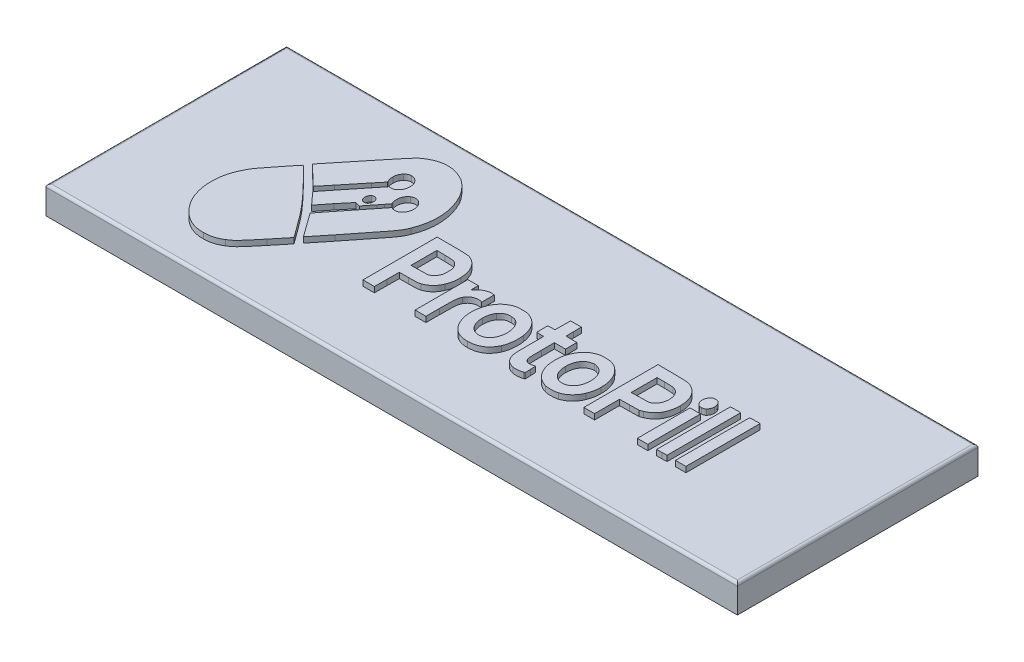
SolidWorks part; units mm, degrees
ref_plane "Front Plane" through (0, 0, 0) normal (0, 0, 1) x (1, 0, 0)
ref_plane "Top Plane" through (0, 0, 0) normal (0, 1, 0) x (1, 0, 0)
ref_plane "Right Plane" through (0, 0, 0) normal (1, 0, 0) x (0, 0, -1)
sketch "Sketch1" plane through (0, 0, 0) normal (0, 1, 0) x (1, 0, 0)
  line L1 (125, -43.5) -> (-125, -43.5)
  line L2 (125, -43.5) -> (125, 43.5)
  line L3 (125, 43.5) -> (-125, 43.5)
  line L4 (-125, -43.5) -> (-125, 43.5)
  line L5 (125, -43.5) -> (-125, 43.5) construction
  line L6 (125, 43.5) -> (-125, -43.5) construction
  point P0 (0, 0)
extrude "Boss-Extrude1" add sketch "Sketch1" along normal blind 10
sketch "Sketch3" plane through (0, 10, 0) normal (0, 1, 0) x (1, 0, 0)
  line L0 (-79.5674, 10.7697) -> (-81.0656, 8.9206)
  line L1 (-81.0656, 8.9206) -> (-79.1545, 7.0857)
  line L2 (-64.4672, 13.6773) -> (-61.8247, 16.8672)
  line L3 (-61.8247, 16.8672) -> (-62.155, 17.5588)
  line L4 (-59.4299, 15.6251) -> (-60.1731, 15.6251)
  line L5 (-60.1731, 15.6251) -> (-61.6949, 13.7055)
  line L6 (-70.9792, -1.2137) -> (-69.5989, -2.7522)
  line L7 (-69.5989, -2.7522) -> (-66.3902, 1.1858)
  line L8 (-62.8039, 5.646) -> (-62.4264, 6.1683)
  line L9 (-62.4264, 6.1683) -> (-62.6033, 6.8175)
  line L10 (-73.952, 2.1173) -> (-72.3476, 0.3954)
  line L11 (-56.5986, 7.8479) -> (-55.4307, 9.3441)
  line L12 (-55.4307, 9.3441) -> (-54.2746, 10.8543)
  line L13 (-54.2746, 10.8543) -> (-54.5224, 11.546)
  line L14 (-52.6467, 9.4429) -> (-53.0831, 9.5981)
  line L15 (-53.0831, 9.5981) -> (-54.0859, 8.356)
  line L16 (-73.4919, 9.6687) -> (-75.757, 6.8599)
  line L17 (-75.757, 6.8599) -> (-76.6535, 7.8338)
  line L18 (-35.659, -4.8271) -> (-35.659, -18.2361)
  line L19 (-35.659, -18.2361) -> (-33.5945, -18.2361)
  line L20 (-33.5945, -18.2361) -> (-31.53, -18.2361)
  line L21 (-31.53, -18.2361) -> (-31.5064, -13.7476)
  line L22 (-31.5064, -13.7476) -> (-31.471, -9.2732)
  line L23 (-31.471, -9.2732) -> (-28.1679, -9.2591)
  line L24 (-30.3149, 8.5819) -> (-35.659, 8.5819)
  line L25 (-35.659, 8.5819) -> (-35.659, -4.8271)
  line L26 (-24.7821, -4.5025) -> (-25.4546, -4.8977)
  line L27 (-25.4546, -4.8977) -> (-28.4864, -4.94)
  line L28 (-28.4864, -4.94) -> (-31.53, -4.9824)
  line L29 (-31.53, -4.9824) -> (-31.53, -0.3104)
  line L30 (-31.53, -0.3104) -> (-31.53, 4.3757)
  line L31 (-31.53, 4.3757) -> (-28.5454, 4.3192)
  line L32 (44.2067, -4.813) -> (44.2067, -18.2361)
  line L33 (44.2067, -18.2361) -> (46.1532, -18.2361)
  line L34 (46.1532, -18.2361) -> (48.0997, -18.2361)
  line L35 (48.0997, -18.2361) -> (48.0997, -13.7335)
  line L36 (48.0997, -13.7335) -> (48.0997, -9.2309)
  line L37 (48.0997, -9.2309) -> (51.6152, -9.1744)
  line L38 (51.6152, -9.1744) -> (55.1189, -9.118)
  line L39 (55.1189, -9.118) -> (56.2279, -8.6663)
  line L40 (49.5508, 8.5536) -> (44.2067, 8.596)
  line L41 (44.2067, 8.596) -> (44.2067, -4.813)
  line L42 (51.2613, -4.94) -> (48.0997, -4.9824)
  line L43 (48.0997, -4.9824) -> (48.0997, -0.3245)
  line L44 (48.0997, -0.3245) -> (48.0997, 4.3475)
  line L45 (48.0997, 4.3475) -> (50.7187, 4.3475)
  line L46 (70.9033, 8.469) -> (70.514, 8.4266)
  line L47 (70.514, 8.4266) -> (70.514, -4.9118)
  line L48 (70.514, -4.9118) -> (70.514, -18.2502)
  line L49 (70.514, -18.2502) -> (72.378, -18.2078)
  line L50 (72.378, -18.2078) -> (74.2301, -18.1655)
  line L51 (74.2301, -18.1655) -> (74.2301, -4.8412)
  line L52 (74.2301, -4.8412) -> (74.2301, 8.4831)
  line L53 (74.2301, 8.4831) -> (72.7555, 8.4972)
  line L54 (77.3563, -4.9259) -> (77.3563, -18.2361)
  line L55 (77.3563, -18.2361) -> (79.2438, -18.2361)
  line L56 (79.2438, -18.2361) -> (81.1313, -18.2361)
  line L57 (81.1313, -18.2361) -> (81.1313, -4.8271)
  line L58 (81.1313, -4.8271) -> (81.1313, 8.596)
  line L59 (81.1313, 8.596) -> (79.3146, 8.5678)
  line L60 (-65.8121, -22.8233) -> (-61.4, -17.4456)
  line L61 (-61.4, -17.4456) -> (-62.7095, -15.6107)
  line L62 (-85.5603, -0.508) -> (-82.3397, 3.5288)
  line L63 (-82.3397, 3.5288) -> (-81.4195, 2.4279)
  line L64 (-81.4195, 2.4279) -> (-80.4994, 1.341)
  line L65 (-80.4994, 1.341) -> (-81.2308, 0.3812)
  line L66 (14.6906, 3.6841) -> (14.6552, 0.8894)
  line L67 (14.6552, 0.8894) -> (13.3812, 0.847)
  line L68 (13.3812, 0.847) -> (12.1071, 0.8047)
  line L69 (12.1071, 0.8047) -> (12.1425, -1.1996)
  line L70 (12.1425, -1.1996) -> (12.1779, -3.2039)
  line L71 (12.1779, -3.2039) -> (13.4519, -3.2462)
  line L72 (13.4519, -3.2462) -> (14.7142, -3.2886)
  line L73 (14.7142, -3.2886) -> (14.7142, -8.3981)
  line L74 (22.2761, -18.0808) -> (22.689, -17.9255)
  line L75 (22.689, -17.9255) -> (22.6418, -15.9918)
  line L76 (18.6308, -8.0311) -> (18.5954, -3.2745)
  line L77 (18.5954, -3.2745) -> (20.6009, -3.2745)
  line L78 (20.6009, -3.2745) -> (22.6182, -3.2745)
  line L79 (22.6182, -3.2745) -> (22.6182, -1.2278)
  line L80 (22.6182, -1.2278) -> (22.6182, 0.8188)
  line L81 (22.6182, 0.8188) -> (20.6481, 0.847)
  line L82 (20.6481, 0.847) -> (18.6662, 0.8894)
  line L83 (18.6662, 0.8894) -> (18.6308, 3.6841)
  line L84 (18.6308, 3.6841) -> (18.6072, 6.4647)
  line L85 (18.6072, 6.4647) -> (16.6607, 6.4647)
  line L86 (16.6607, 6.4647) -> (14.7142, 6.4647)
  line L87 (14.7142, 6.4647) -> (14.6906, 3.6841)
  line L88 (-67.8058, -4.8271) -> (-67.2631, -5.4622)
  line L89 (-67.2631, -5.4622) -> (-66.0009, -3.9096)
  line L90 (-62.1078, 0.9599) -> (-59.4771, 4.2628)
  line L91 (-59.4771, 4.2628) -> (-60.1613, 4.4322)
  line L92 (-13.0087, -0.5221) -> (-13.0087, 0.8188)
  line L93 (-13.0087, 0.8188) -> (-14.8963, 0.8188)
  line L94 (-14.8963, 0.8188) -> (-16.7838, 0.8188)
  line L95 (-16.7838, 0.8188) -> (-16.7838, -8.7086)
  line L96 (-16.7838, -8.7086) -> (-16.7838, -18.2361)
  line L97 (-16.7838, -18.2361) -> (-14.8373, -18.2361)
  line L98 (-14.8373, -18.2361) -> (-12.8908, -18.2361)
  line L99 (-12.8908, -18.2361) -> (-12.8908, -13.2536)
  line L100 (-7.6647, -3.5991) -> (-7.2282, -3.712)
  line L101 (-7.2282, -3.712) -> (-7.2282, -1.4396)
  line L102 (-7.2282, -1.4396) -> (-7.2282, 0.8188)
  line L103 (-7.2282, 0.8188) -> (-7.5113, 0.8188)
  line L104 (63.5538, -8.7086) -> (63.5538, -18.2361)
  line L105 (63.5538, -18.2361) -> (65.4413, -18.2361)
  line L106 (65.4413, -18.2361) -> (67.3288, -18.2361)
  line L107 (67.3288, -18.2361) -> (67.3288, -8.7086)
  line L108 (67.3288, -8.7086) -> (67.3288, 0.8188)
  line L109 (67.3288, 0.8188) -> (65.4413, 0.8188)
  line L110 (65.4413, 0.8188) -> (63.5538, 0.8188)
  line L111 (63.5538, 0.8188) -> (63.5538, -8.7086)
  line L112 (-69.5989, -2.7522) -> (-68.3367, -4.1072)
  line L113 (-67.2631, -5.4622) -> (-66.0952, -6.8455)
  line L114 (-56.5986, 7.8479) -> (-59.4771, 4.2628)
  line L115 (-60.9989, 11.4613) -> (-58.8873, 9.6687)
  spline S0 degree 3 poles (-58.2502, 32.6192) (-60.2557, 32.1958) (-62.5561, 31.0101) (-64.0897, 29.6269) knots 0 0 0 0 1 1 1 1
  spline S1 degree 3 poles (-64.0897, 29.6269) (-64.5144, 29.2458) (-67.8294, 25.2655) (-71.4629, 20.777) knots 0 0 0 0 1 1 1 1
  spline S2 degree 3 poles (-71.4629, 20.777) (-75.0963, 16.2744) (-78.7416, 11.7718) (-79.5674, 10.7697) knots 0 0 0 0 1 1 1 1
  spline S3 degree 3 poles (-79.1545, 7.0857) (-78.1046, 6.0836) (-76.5356, 4.5451) (-75.6626, 3.67) knots 0 0 0 0 1 1 1 1
  spline S4 degree 3 poles (-75.6626, 3.67) (-74.7896, 2.7948) (-74.0228, 2.1032) (-73.952, 2.1173) knots 0 0 0 0 1 1 1 1
  spline S5 degree 3 poles (-73.952, 2.1173) (-73.8695, 2.1456) (-72.3122, 4.0369) (-70.4719, 6.3235) knots 0 0 0 0 1 1 1 1
  spline S6 degree 3 poles (-70.4719, 6.3235) (-68.6198, 8.6101) (-65.9301, 11.9271) (-64.4672, 13.6773) knots 0 0 0 0 1 1 1 1
  spline S7 degree 3 poles (-62.155, 17.5588) (-62.45, 18.1658) (-62.4971, 18.3916) (-62.4971, 19.3796) knots 0 0 0 0 1 1 1 1
  spline S8 degree 3 poles (-62.4971, 19.3796) (-62.4971, 20.7064) (-62.2612, 21.3557) (-61.4944, 22.1884) knots 0 0 0 0 1 1 1 1
  spline S9 degree 3 poles (-61.4944, 22.1884) (-60.8338, 22.9083) (-60.2793, 23.1624) (-59.4299, 23.1624) knots 0 0 0 0 1 1 1 1
  spline S10 degree 3 poles (-59.4299, 23.1624) (-58.5452, 23.1765) (-57.8255, 22.8095) (-57.1649, 22.005) knots 0 0 0 0 1 1 1 1
  spline S11 degree 3 poles (-57.1649, 22.005) (-56.4807, 21.1722) (-56.2565, 20.4241) (-56.3273, 19.0973) knots 0 0 0 0 1 1 1 1
  spline S12 degree 3 poles (-56.3273, 19.0973) (-56.3745, 18.2504) (-56.4453, 17.9258) (-56.7166, 17.46) knots 0 0 0 0 1 1 1 1
  spline S13 degree 3 poles (-56.7166, 17.46) (-57.4244, 16.1615) (-58.2384, 15.611) (-59.4299, 15.6251) knots 0 0 0 0 1 1 1 1
  spline S14 degree 3 poles (-61.6949, 13.7055) (-62.5207, 12.6469) (-65.2576, 9.2312) (-67.7704, 6.1259) knots 0 0 0 0 1 1 1 1
  spline S15 degree 3 poles (-67.7704, 6.1259) (-70.295, 3.0207) (-72.3476, 0.4377) (-72.3476, 0.3954) knots 0 0 0 0 1 1 1 1
  spline S16 degree 3 poles (-72.3476, 0.3954) (-72.3476, 0.3389) (-71.7342, -0.381) (-70.9792, -1.2137) knots 0 0 0 0 1 1 1 1
  spline S17 degree 3 poles (-66.3902, 1.1858) (-64.6324, 3.3594) (-63.0162, 5.3637) (-62.8039, 5.646) knots 0 0 0 0 1 1 1 1
  spline S18 degree 3 poles (-62.6033, 6.8175) (-63.1224, 8.6242) (-62.4382, 10.6003) (-60.9989, 11.4613) knots 0 0 0 0 1 1 1 1
  spline S19 degree 3 poles (-54.5224, 11.546) (-55.1712, 13.3526) (-54.5696, 15.4557) (-53.1303, 16.3873) knots 0 0 0 0 1 1 1 1
  spline S20 degree 3 poles (-53.1303, 16.3873) (-51.9034, 17.1918) (-50.6058, 16.9801) (-49.5558, 15.8227) knots 0 0 0 0 1 1 1 1
  spline S21 degree 3 poles (-49.5558, 15.8227) (-47.8925, 13.9455) (-48.4233, 10.572) (-50.5704, 9.4993) knots 0 0 0 0 1 1 1 1
  spline S22 degree 3 poles (-50.5704, 9.4993) (-51.0659, 9.2453) (-52.0332, 9.2312) (-52.6467, 9.4429) knots 0 0 0 0 1 1 1 1
  spline S23 degree 3 poles (-54.0859, 8.356) (-54.9943, 7.2128) (-58.5216, 2.7666) (-63.9954, -4.1072) knots 0 0 0 0 1 1 1 1
  spline S24 degree 3 poles (-63.9954, -4.1072) (-65.1515, -5.5469) (-66.0952, -6.789) (-66.0952, -6.8455) knots 0 0 0 0 1 1 1 1
  spline S25 degree 3 poles (-66.0952, -6.8455) (-66.0952, -6.9161) (-65.3874, -7.9323) (-64.5262, -9.1038) knots 0 0 0 0 1 1 1 1
  spline S26 degree 3 poles (-64.5262, -9.1038) (-63.665, -10.2895) (-62.2966, -12.1667) (-61.5062, -13.2959) knots 0 0 0 0 1 1 1 1
  spline S27 degree 3 poles (-61.5062, -13.2959) (-60.704, -14.4251) (-60.008, -15.3849) (-59.9726, -15.4413) knots 0 0 0 0 1 1 1 1
  spline S28 degree 3 poles (-59.9726, -15.4413) (-59.9254, -15.5119) (-57.6014, -12.6749) (-54.8173, -9.1603) knots 0 0 0 0 1 1 1 1
  spline S29 degree 3 poles (-54.8173, -9.1603) (-44.0112, 4.418) (-44.377, 3.9099) (-43.2208, 6.7046) knots 0 0 0 0 1 1 1 1
  spline S30 degree 3 poles (-43.2208, 6.7046) (-40.7317, 12.6751) (-41.0974, 19.4361) (-44.2236, 25.1949) knots 0 0 0 0 1 1 1 1
  spline S31 degree 3 poles (-44.2236, 25.1949) (-45.3915, 27.3544) (-47.5975, 29.768) (-49.4733, 30.9537) knots 0 0 0 0 1 1 1 1
  spline S32 degree 3 poles (-49.4733, 30.9537) (-50.5114, 31.603) (-52.4579, 32.3651) (-53.7556, 32.6474) knots 0 0 0 0 1 1 1 1
  spline S33 degree 3 poles (-53.7556, 32.6474) (-55.0296, 32.9015) (-56.9761, 32.9015) (-58.2502, 32.6192) knots 0 0 0 0 1 1 1 1
  spline S34 degree 3 poles (-53.2955, 29.6834) (-50.7473, 29.0482) (-48.4705, 27.3403) (-46.7246, 24.715) knots 0 0 0 0 1 1 1 1
  spline S35 degree 3 poles (-46.7246, 24.715) (-45.7926, 23.3176) (-44.8134, 20.8617) (-45.1791, 20.8617) knots 0 0 0 0 1 1 1 1
  spline S36 degree 3 poles (-45.1791, 20.8617) (-45.2263, 20.8617) (-45.7454, 21.4545) (-46.3471, 22.1884) knots 0 0 0 0 1 1 1 1
  spline S37 degree 3 poles (-46.3471, 22.1884) (-49.603, 26.1406) (-54.0859, 27.8626) (-58.0143, 26.6487) knots 0 0 0 0 1 1 1 1
  spline S38 degree 3 poles (-58.0143, 26.6487) (-59.2648, 26.2676) (-60.9163, 25.2796) (-61.8719, 24.3198) knots 0 0 0 0 1 1 1 1
  spline S39 degree 3 poles (-61.8719, 24.3198) (-62.3084, 23.8963) (-63.5589, 22.3296) (-64.656, 20.8334) knots 0 0 0 0 1 1 1 1
  spline S40 degree 3 poles (-64.656, 20.8334) (-66.5199, 18.2928) (-67.6406, 16.8813) (-73.4919, 9.6687) knots 0 0 0 0 1 1 1 1
  spline S41 degree 3 poles (-76.6535, 7.8338) (-77.1372, 8.356) (-77.5383, 8.8218) (-77.5383, 8.8642) knots 0 0 0 0 1 1 1 1
  spline S42 degree 3 poles (-77.5383, 8.8642) (-77.5383, 8.9065) (-75.5092, 11.433) (-73.0201, 14.4536) knots 0 0 0 0 1 1 1 1
  spline S43 degree 3 poles (-73.0201, 14.4536) (-70.5427, 17.4883) (-67.3457, 21.4121) (-65.9183, 23.1765) knots 0 0 0 0 1 1 1 1
  spline S44 degree 3 poles (-65.9183, 23.1765) (-62.5915, 27.298) (-61.5652, 28.2437) (-59.3709, 29.2035) knots 0 0 0 0 1 1 1 1
  spline S45 degree 3 poles (-59.3709, 29.2035) (-57.448, 30.0362) (-55.4189, 30.2056) (-53.2955, 29.6834) knots 0 0 0 0 1 1 1 1
  spline S46 degree 3 poles (-60.2911, 21.0028) (-61.2467, 20.2971) (-61.2349, 18.4763) (-60.2557, 17.7564) knots 0 0 0 0 1 1 1 1
  spline S47 degree 3 poles (-60.2557, 17.7564) (-59.194, 16.9801) (-57.8373, 17.8835) (-57.8373, 19.3796) knots 0 0 0 0 1 1 1 1
  spline S48 degree 3 poles (-57.8373, 19.3796) (-57.8373, 20.8758) (-59.2058, 21.7932) (-60.2911, 21.0028) knots 0 0 0 0 1 1 1 1
  spline S49 degree 3 poles (-52.3635, 14.7923) (-52.4933, 14.7359) (-52.7528, 14.4818) (-52.918, 14.2278) knots 0 0 0 0 1 1 1 1
  spline S50 degree 3 poles (-52.918, 14.2278) (-53.1657, 13.889) (-53.2365, 13.6349) (-53.2365, 13.1268) knots 0 0 0 0 1 1 1 1
  spline S51 degree 3 poles (-53.2365, 13.1268) (-53.2365, 12.294) (-53.0477, 11.8565) (-52.5405, 11.4472) knots 0 0 0 0 1 1 1 1
  spline S52 degree 3 poles (-52.5405, 11.4472) (-51.5495, 10.6426) (-50.1575, 11.5036) (-50.1221, 12.9292) knots 0 0 0 0 1 1 1 1
  spline S53 degree 3 poles (-50.1221, 12.9292) (-50.1103, 13.6773) (-50.3698, 14.3266) (-50.8181, 14.6512) knots 0 0 0 0 1 1 1 1
  spline S54 degree 3 poles (-50.8181, 14.6512) (-51.2074, 14.9476) (-51.9152, 15.0041) (-52.3635, 14.7923) knots 0 0 0 0 1 1 1 1
  spline S55 degree 3 poles (-60.5152, 9.7111) (-61.5652, 8.9489) (-61.4826, 7.0293) (-60.3737, 6.4082) knots 0 0 0 0 1 1 1 1
  spline S56 degree 3 poles (-60.3737, 6.4082) (-59.3591, 5.8295) (-58.1912, 6.7329) (-58.1912, 8.0879) knots 0 0 0 0 1 1 1 1
  spline S57 degree 3 poles (-58.1912, 8.0879) (-58.1912, 8.8218) (-58.3918, 9.2735) (-58.8873, 9.6687) knots 0 0 0 0 1 1 1 1
  spline S58 degree 3 poles (-58.8873, 9.6687) (-59.3827, 10.0639) (-60.008, 10.0921) (-60.5152, 9.7111) knots 0 0 0 0 1 1 1 1
  spline S59 degree 3 poles (-28.1679, -9.2591) (-25.195, -9.245) (-24.7703, -9.2168) (-23.9445, -8.9486) knots 0 0 0 0 1 1 1 1
  spline S60 degree 3 poles (-23.9445, -8.9486) (-21.9155, -8.2852) (-20.3819, -6.8173) (-19.5089, -4.6859) knots 0 0 0 0 1 1 1 1
  spline S61 degree 3 poles (-19.5089, -4.6859) (-18.8482, -3.0628) (-18.6359, -1.7783) (-18.7067, 0.1836) knots 0 0 0 0 1 1 1 1
  spline S62 degree 3 poles (-18.7067, 0.1836) (-18.8364, 3.6982) (-20.1577, 6.2812) (-22.5053, 7.6785) knots 0 0 0 0 1 1 1 1
  spline S63 degree 3 poles (-22.5053, 7.6785) (-23.9563, 8.5254) (-24.3692, 8.5819) (-30.3149, 8.5819) knots 0 0 0 0 1 1 1 1
  spline S64 degree 3 poles (-25.0299, 4.0087) (-24.2867, 3.6841) (-23.567, 2.9078) (-23.1777, 2.0327) knots 0 0 0 0 1 1 1 1
  spline S65 degree 3 poles (-23.1777, 2.0327) (-22.8828, 1.3834) (-22.8592, 1.1717) (-22.8592, -0.2398) knots 0 0 0 0 1 1 1 1
  spline S66 degree 3 poles (-22.8592, -0.2398) (-22.8592, -1.5242) (-22.9064, -1.9053) (-23.107, -2.4417) knots 0 0 0 0 1 1 1 1
  spline S67 degree 3 poles (-23.107, -2.4417) (-23.4727, -3.3733) (-24.0271, -4.0508) (-24.7821, -4.5025) knots 0 0 0 0 1 1 1 1
  spline S68 degree 3 poles (-28.5454, 4.3192) (-26.0798, 4.2628) (-25.4782, 4.2204) (-25.0299, 4.0087) knots 0 0 0 0 1 1 1 1
  spline S69 degree 3 poles (56.2279, -8.6663) (59.4366, -7.3395) (61.1236, -4.4319) (61.1236, -0.2398) knots 0 0 0 0 1 1 1 1
  spline S70 degree 3 poles (61.1236, -0.2398) (61.1236, 2.4138) (60.463, 4.3757) (59.0238, 6.013) knots 0 0 0 0 1 1 1 1
  spline S71 degree 3 poles (59.0238, 6.013) (58.0446, 7.1139) (57.089, 7.7632) (55.8032, 8.1867) knots 0 0 0 0 1 1 1 1
  spline S72 degree 3 poles (55.8032, 8.1867) (54.9302, 8.4831) (54.5763, 8.4972) (49.5508, 8.5536) knots 0 0 0 0 1 1 1 1
  spline S73 degree 3 poles (54.069, 4.1922) (55.5436, 3.8817) (56.6408, 2.696) (57.0065, 1.0305) knots 0 0 0 0 1 1 1 1
  spline S74 degree 3 poles (57.0065, 1.0305) (57.2424, -0.0987) (57.2306, -0.8044) (56.9357, -1.9336) knots 0 0 0 0 1 1 1 1
  spline S75 degree 3 poles (56.9357, -1.9336) (56.6408, -3.1051) (55.9329, -4.079) (55.0246, -4.5589) knots 0 0 0 0 1 1 1 1
  spline S76 degree 3 poles (55.0246, -4.5589) (54.4347, -4.8835) (54.2696, -4.8977) (51.2613, -4.94) knots 0 0 0 0 1 1 1 1
  spline S77 degree 3 poles (50.7187, 4.3475) (52.1579, 4.3475) (53.6679, 4.2769) (54.069, 4.1922) knots 0 0 0 0 1 1 1 1
  spline S78 degree 3 poles (72.7555, 8.4972) (71.9415, 8.5113) (71.1039, 8.4972) (70.9033, 8.469) knots 0 0 0 0 1 1 1 1
  spline S79 degree 3 poles (77.4271, 8.469) (77.3917, 8.4266) (77.3563, 2.3996) (77.3563, -4.9259) knots 0 0 0 0 1 1 1 1
  spline S80 degree 3 poles (79.3146, 8.5678) (78.3118, 8.5678) (77.4625, 8.5254) (77.4271, 8.469) knots 0 0 0 0 1 1 1 1
  spline S81 degree 3 poles (64.6155, 8.0032) (63.424, 7.4386) (62.905, 5.5613) (63.5774, 4.1922) knots 0 0 0 0 1 1 1 1
  spline S82 degree 3 poles (63.5774, 4.1922) (64.0257, 3.2747) (64.6627, 2.8937) (65.6183, 2.9642) knots 0 0 0 0 1 1 1 1
  spline S83 degree 3 poles (65.6183, 2.9642) (66.2435, 3.0066) (66.4559, 3.0913) (66.8216, 3.4441) knots 0 0 0 0 1 1 1 1
  spline S84 degree 3 poles (66.8216, 3.4441) (67.3996, 3.9946) (67.6827, 4.6721) (67.6827, 5.5049) knots 0 0 0 0 1 1 1 1
  spline S85 degree 3 poles (67.6827, 5.5049) (67.6827, 6.6482) (67.2227, 7.5515) (66.4205, 7.9608) knots 0 0 0 0 1 1 1 1
  spline S86 degree 3 poles (66.4205, 7.9608) (65.984, 8.1867) (65.052, 8.2008) (64.6155, 8.0032) knots 0 0 0 0 1 1 1 1
  spline S87 degree 3 poles (-86.1029, 2.2867) (-88.1084, -0.2539) (-89.9724, -2.6534) (-90.2555, -3.0486) knots 0 0 0 0 1 1 1 1
  spline S88 degree 3 poles (-90.2555, -3.0486) (-91.4588, -4.7565) (-92.6621, -7.4101) (-93.2873, -9.6967) knots 0 0 0 0 1 1 1 1
  spline S89 degree 3 poles (-93.2873, -9.6967) (-94.1721, -12.9713) (-94.1485, -16.9375) (-93.2283, -20.2403) knots 0 0 0 0 1 1 1 1
  spline S90 degree 3 poles (-93.2283, -20.2403) (-92.5205, -22.781) (-91.4942, -24.7853) (-89.8898, -26.7896) knots 0 0 0 0 1 1 1 1
  spline S91 degree 3 poles (-89.8898, -26.7896) (-86.9287, -30.5017) (-83.5194, -32.2661) (-79.3669, -32.252) knots 0 0 0 0 1 1 1 1
  spline S92 degree 3 poles (-79.3669, -32.252) (-77.0193, -32.2378) (-75.2025, -31.7156) (-73.1026, -30.4312) knots 0 0 0 0 1 1 1 1
  spline S93 degree 3 poles (-73.1026, -30.4312) (-71.2033, -29.2737) (-70.4483, -28.4833) (-65.8121, -22.8233) knots 0 0 0 0 1 1 1 1
  spline S94 degree 3 poles (-62.7095, -15.6107) (-67.0862, -9.4849) (-69.1742, -6.8455) (-72.7016, -2.9922) knots 0 0 0 0 1 1 1 1
  spline S95 degree 3 poles (-72.7016, -2.9922) (-75.7806, 0.3812) (-81.9622, 6.6764) (-82.3751, 6.8599) knots 0 0 0 0 1 1 1 1
  spline S96 degree 3 poles (-82.3751, 6.8599) (-82.4223, 6.874) (-84.0975, 4.8274) (-86.1029, 2.2867) knots 0 0 0 0 1 1 1 1
  spline S97 degree 3 poles (-81.2308, 0.3812) (-81.6319, -0.141) (-82.8706, -1.736) (-83.9913, -3.1616) knots 0 0 0 0 1 1 1 1
  spline S98 degree 3 poles (-83.9913, -3.1616) (-85.1002, -4.5871) (-86.3861, -6.2809) (-86.8344, -6.9302) knots 0 0 0 0 1 1 1 1
  spline S99 degree 3 poles (-86.8344, -6.9302) (-88.828, -9.8096) (-89.9016, -12.9289) (-90.1257, -16.5423) knots 0 0 0 0 1 1 1 1
  spline S100 degree 3 poles (-90.1257, -16.5423) (-90.2201, -17.982) (-90.2319, -18.0243) (-90.5032, -18.0243) knots 0 0 0 0 1 1 1 1
  spline S101 degree 3 poles (-90.5032, -18.0243) (-90.751, -18.0243) (-90.8453, -17.8973) (-91.0577, -17.248) knots 0 0 0 0 1 1 1 1
  spline S102 degree 3 poles (-91.0577, -17.248) (-91.4234, -16.1612) (-91.6947, -14.4815) (-91.6947, -13.3241) knots 0 0 0 0 1 1 1 1
  spline S103 degree 3 poles (-91.6947, -13.3241) (-91.6947, -11.4045) (-91.1285, -8.8357) (-90.3381, -7.1419) knots 0 0 0 0 1 1 1 1
  spline S104 degree 3 poles (-90.3381, -7.1419) (-89.701, -5.801) (-89.0758, -4.9118) (-85.5603, -0.508) knots 0 0 0 0 1 1 1 1
  spline S105 degree 3 poles (14.7142, -8.3981) (14.7142, -12.9289) (14.7378, -13.6205) (14.9266, -14.4533) knots 0 0 0 0 1 1 1 1
  spline S106 degree 3 poles (14.9266, -14.4533) (15.4692, -16.7822) (16.7197, -18.0384) (18.8432, -18.4054) knots 0 0 0 0 1 1 1 1
  spline S107 degree 3 poles (18.8432, -18.4054) (19.8459, -18.5748) (21.3323, -18.4337) (22.2761, -18.0808) knots 0 0 0 0 1 1 1 1
  spline S108 degree 3 poles (22.6418, -15.9918) (22.6182, -14.9332) (22.5828, -14.0581) (22.5592, -14.0299) knots 0 0 0 0 1 1 1 1
  spline S109 degree 3 poles (22.5592, -14.0299) (22.5474, -14.0158) (22.2289, -14.0863) (21.8396, -14.2134) knots 0 0 0 0 1 1 1 1
  spline S110 degree 3 poles (21.8396, -14.2134) (20.4594, -14.6368) (19.4684, -14.3404) (18.9493, -13.3524) knots 0 0 0 0 1 1 1 1
  spline S111 degree 3 poles (18.9493, -13.3524) (18.6662, -12.8019) (18.6662, -12.7878) (18.6308, -8.0311) knots 0 0 0 0 1 1 1 1
  spline S112 degree 3 poles (-64.7858, 0.3954) (-66.7323, -2.0324) (-68.3367, -4.0508) (-68.3367, -4.1072) knots 0 0 0 0 1 1 1 1
  spline S113 degree 3 poles (-68.3367, -4.1072) (-68.3367, -4.1637) (-68.1007, -4.4883) (-67.8058, -4.8271) knots 0 0 0 0 1 1 1 1
  spline S114 degree 3 poles (-66.0009, -3.9096) (-65.3048, -3.0486) (-63.5471, -0.8609) (-62.1078, 0.9599) knots 0 0 0 0 1 1 1 1
  spline S115 degree 3 poles (-60.1613, 4.4322) (-60.5388, 4.531) (-60.9281, 4.6439) (-61.0343, 4.7003) knots 0 0 0 0 1 1 1 1
  spline S116 degree 3 poles (-61.0343, 4.7003) (-61.1759, 4.7568) (-62.1668, 3.6276) (-64.7858, 0.3954) knots 0 0 0 0 1 1 1 1
  spline S117 degree 3 poles (0.3691, 1.0446) (-2.533, 0.2542) (-4.5975, -1.8912) (-5.5176, -5.067) knots 0 0 0 0 1 1 1 1
  spline S118 degree 3 poles (-5.5176, -5.067) (-6.9687, -10.0495) (-5.3289, -15.4131) (-1.719, -17.5303) knots 0 0 0 0 1 1 1 1
  spline S119 degree 3 poles (-1.719, -17.5303) (-0.4331, -18.2784) (0.6404, -18.5466) (2.3864, -18.5466) knots 0 0 0 0 1 1 1 1
  spline S120 degree 3 poles (2.3864, -18.5466) (6.008, -18.5607) (8.5444, -16.9516) (9.9836, -13.7335) knots 0 0 0 0 1 1 1 1
  spline S121 degree 3 poles (9.9836, -13.7335) (10.8094, -11.8703) (11.1279, -9.0756) (10.774, -6.6902) knots 0 0 0 0 1 1 1 1
  spline S122 degree 3 poles (10.774, -6.6902) (10.2314, -2.9498) (8.4382, -0.4374) (5.489, 0.7482) knots 0 0 0 0 1 1 1 1
  spline S123 degree 3 poles (5.489, 0.7482) (4.6396, 1.087) (4.2857, 1.1434) (2.7992, 1.1858) knots 0 0 0 0 1 1 1 1
  spline S124 degree 3 poles (2.7992, 1.1858) (1.6195, 1.2281) (0.8645, 1.1717) (0.3691, 1.0446) knots 0 0 0 0 1 1 1 1
  spline S125 degree 3 poles (4.4744, -3.3027) (5.7957, -4.0367) (6.5625, -5.3352) (6.9046, -7.4242) knots 0 0 0 0 1 1 1 1
  spline S126 degree 3 poles (6.9046, -7.4242) (7.2585, -9.5837) (6.7041, -11.9409) (5.5362, -13.1548) knots 0 0 0 0 1 1 1 1
  spline S127 degree 3 poles (5.5362, -13.1548) (4.8755, -13.8605) (4.4744, -14.1287) (3.684, -14.3686) knots 0 0 0 0 1 1 1 1
  spline S128 degree 3 poles (3.684, -14.3686) (1.8083, -14.9756) (-0.1854, -14.1287) (-1.2117, -12.2797) knots 0 0 0 0 1 1 1 1
  spline S129 degree 3 poles (-1.2117, -12.2797) (-1.837, -11.1505) (-2.0847, -10.1201) (-2.0847, -8.6381) knots 0 0 0 0 1 1 1 1
  spline S130 degree 3 poles (-2.0847, -8.6381) (-2.0847, -6.8878) (-1.7426, -5.6457) (-0.964, -4.6295) knots 0 0 0 0 1 1 1 1
  spline S131 degree 3 poles (-0.964, -4.6295) (0.1213, -3.2039) (0.8763, -2.8369) (2.6223, -2.8934) knots 0 0 0 0 1 1 1 1
  spline S132 degree 3 poles (2.6223, -2.8934) (3.6132, -2.9216) (3.9082, -2.9781) (4.4744, -3.3027) knots 0 0 0 0 1 1 1 1
  spline S133 degree 3 poles (30.4632, 1.0164) (29.4723, 0.7482) (28.2218, 0.1413) (27.5376, -0.4374) knots 0 0 0 0 1 1 1 1
  spline S134 degree 3 poles (27.5376, -0.4374) (26.0275, -1.6795) (24.7299, -4.0367) (24.317, -6.295) knots 0 0 0 0 1 1 1 1
  spline S135 degree 3 poles (24.317, -6.295) (24.0338, -7.89) (24.1282, -10.4165) (24.5411, -11.955) knots 0 0 0 0 1 1 1 1
  spline S136 degree 3 poles (24.5411, -11.955) (25.4259, -15.2155) (27.5258, -17.5162) (30.3806, -18.3207) knots 0 0 0 0 1 1 1 1
  spline S137 degree 3 poles (30.3806, -18.3207) (31.5485, -18.6595) (33.8608, -18.6172) (35.0405, -18.2502) knots 0 0 0 0 1 1 1 1
  spline S138 degree 3 poles (35.0405, -18.2502) (37.3409, -17.5303) (39.134, -15.8366) (40.125, -13.4229) knots 0 0 0 0 1 1 1 1
  spline S139 degree 3 poles (40.125, -13.4229) (40.7738, -11.8421) (41.0215, -10.6) (41.0215, -8.751) knots 0 0 0 0 1 1 1 1
  spline S140 degree 3 poles (41.0215, -8.751) (41.0215, -6.9019) (40.7738, -5.5752) (40.125, -3.9943) knots 0 0 0 0 1 1 1 1
  spline S141 degree 3 poles (40.125, -3.9943) (39.6885, -2.9357) (39.3935, -2.4417) (38.6739, -1.5807) knots 0 0 0 0 1 1 1 1
  spline S142 degree 3 poles (38.6739, -1.5807) (37.6594, -0.3527) (36.9044, 0.2119) (35.5359, 0.7623) knots 0 0 0 0 1 1 1 1
  spline S143 degree 3 poles (35.5359, 0.7623) (34.7337, 1.087) (34.3562, 1.1434) (32.9406, 1.1858) knots 0 0 0 0 1 1 1 1
  spline S144 degree 3 poles (32.9406, 1.1858) (31.7491, 1.2281) (31.0649, 1.1717) (30.4632, 1.0164) knots 0 0 0 0 1 1 1 1
  spline S145 degree 3 poles (33.4125, -2.8651) (35.7365, -3.3733) (37.1285, -5.6034) (37.1285, -8.7933) knots 0 0 0 0 1 1 1 1
  spline S146 degree 3 poles (37.1285, -8.7933) (37.1285, -12.3643) (35.0522, -14.778) (32.2092, -14.5239) knots 0 0 0 0 1 1 1 1
  spline S147 degree 3 poles (32.2092, -14.5239) (29.7554, -14.2981) (28.0448, -11.9127) (28.0448, -8.7227) knots 0 0 0 0 1 1 1 1
  spline S148 degree 3 poles (28.0448, -8.7227) (28.0448, -5.2364) (29.7318, -2.9781) (32.5395, -2.724) knots 0 0 0 0 1 1 1 1
  spline S149 degree 3 poles (32.5395, -2.724) (32.6339, -2.724) (33.035, -2.7805) (33.4125, -2.8651) knots 0 0 0 0 1 1 1 1
  spline S150 degree 3 poles (-8.8798, 0.8188) (-10.26, 0.6212) (-11.5577, -0.1269) (-12.3953, -1.2137) knots 0 0 0 0 1 1 1 1
  spline S151 degree 3 poles (-12.3953, -1.2137) (-12.6666, -1.5666) (-12.9262, -1.863) (-12.9497, -1.863) knots 0 0 0 0 1 1 1 1
  spline S152 degree 3 poles (-12.9497, -1.863) (-12.9851, -1.863) (-13.0087, -1.2561) (-13.0087, -0.5221) knots 0 0 0 0 1 1 1 1
  spline S153 degree 3 poles (-12.8908, -13.2536) (-12.8908, -7.8476) (-12.8082, -6.8737) (-12.2419, -5.7445) knots 0 0 0 0 1 1 1 1
  spline S154 degree 3 poles (-12.2419, -5.7445) (-11.4279, -4.0649) (-9.4696, -3.1474) (-7.6647, -3.5991) knots 0 0 0 0 1 1 1 1
  spline S155 degree 3 poles (-7.5113, 0.8188) (-7.6647, 0.8188) (-7.8652, 0.847) (-7.9596, 0.8753) knots 0 0 0 0 1 1 1 1
  spline S156 degree 3 poles (-7.9596, 0.8753) (-8.0422, 0.9035) (-8.4551, 0.8753) (-8.8798, 0.8188) knots 0 0 0 0 1 1 1 1
extrude "Boss-Extrude2" add sketch "Sketch3" along normal blind 2
sketch "Sketch5" plane through (0, 0, 0) normal (0, -1, 0) x (1, 0, 0)
  line L0 (-125.564, 44.1969) -> (-117.5626, 36.1961) construction
  line L1 (-38.5788, 36.1961) -> (-38.5788, 44.1969) construction
  line L2 (-38.5788, 40.1965) -> (-125.564, 40.1965) construction
  line L3 (-117.5626, -0.0776) -> (-125.564, -0.0776) construction
  line L4 (-117.5626, -36.3513) -> (-125.564, -44.3521) construction
  line L5 (-38.5788, -36.3513) -> (-38.5788, -44.3521) construction
  line L6 (117.4013, -36.3513) -> (125.4027, -44.3521) construction
  line L7 (117.4013, -0.0776) -> (125.4027, -0.0776) construction
  line L8 (117.4013, 36.1961) -> (125.4027, 44.1969) construction
  line L9 (1.1092, 40.1965) -> (125.4027, 40.1965) construction
  line L10 (63.2559, 40.1965) -> (63.2559, -44.3521) construction
  line L11 (-38.5788, -40.3517) -> (125.4027, -40.3517) construction
  line L12 (-121.5633, -40.3517) -> (0.875, -40.3517) construction
  line L13 (-38.5788, 40.1965) -> (1.1092, 40.1965) construction
  circle A0 centre (-121.5633, 40.1965) radius 3.075
  circle A1 centre (-121.5633, -0.0776) radius 3.075
  circle A2 centre (-121.5633, -40.3517) radius 3.075
  circle A3 centre (-38.5788, -40.3517) radius 3.075
  circle A4 centre (63.2559, -40.3517) radius 3.075
  circle A5 centre (121.402, -40.3517) radius 3.075
  circle A6 centre (121.402, -0.0776) radius 3.075
  circle A7 centre (121.402, 40.1965) radius 3.075
  circle A8 centre (63.2559, 40.1965) radius 3.075
  circle A9 centre (-38.5788, 40.1965) radius 3.075
extrude "Cut-Extrude1" cut sketch "Sketch5" against normal blind 3
fillet "Fillet1" radius 1 4 edges at (125, 10, 0) (0, 10, -43.5) (-125, 10, 0) (0, 10, 43.5)
